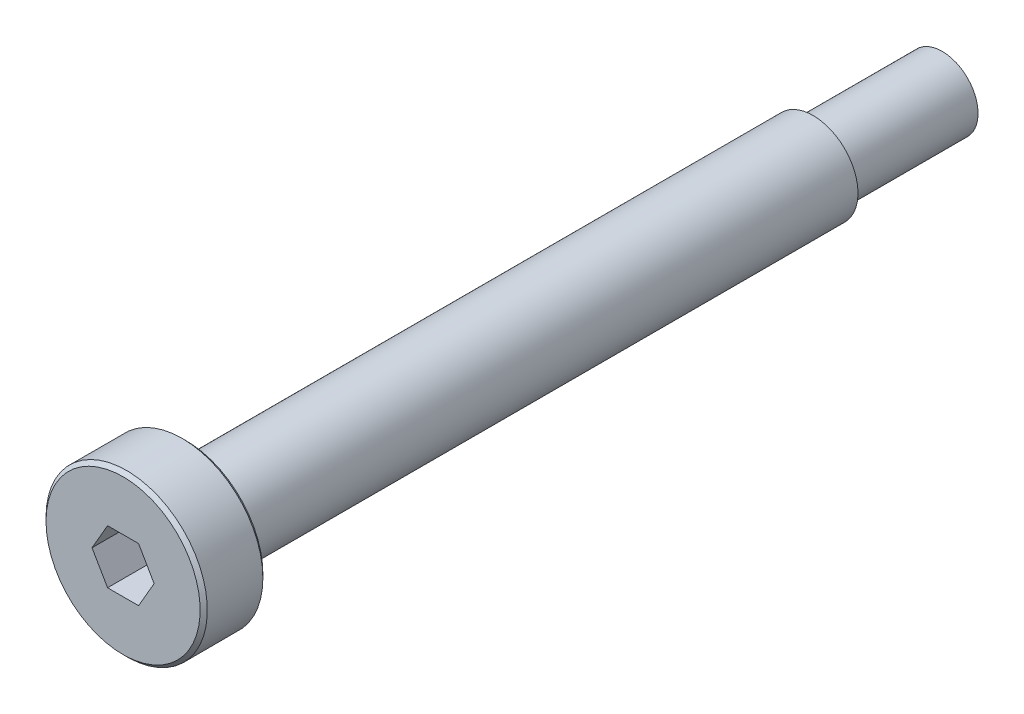
SolidWorks part; units mm, degrees
material "AISI 304"
ref_plane "前视基准面" through (0, 0, 0) normal (1, 0, 0) x (0, 1, 0)
ref_plane "上视基准面" through (0, 0, 0) normal (0, 0, 1) x (0, 1, 0)
ref_plane "右视基准面" through (0, 0, 0) normal (0, 1, 0) x (-1, 0, 0)
other "Configuration Table"
sketch "草图1" plane through (0, 0, 0) normal (1, 0, 0) x (0, 1, 0)
  line L0 (0, 0) -> (-4.5, 0)
  line L1 (-4.5, 0) -> (-4.5, -3.5)
  line L2 (-4.5, -3.5) -> (-2.5, -3.5)
  line L3 (-2.5, -3.5) -> (-2.5, -38.5)
  line L4 (-2.5, -38.5) -> (-2, -38.5)
  line L5 (-2, -38.5) -> (-2, -45.7)
  line L6 (-2, -45.7) -> (0, -45.7)
  line L7 (0, -45.7) -> (0, 0)
  point P8 (-2.25, -38.5)
  dimension "D1" = 3.5
  dimension "D2" = 35
  dimension "D3" = 7.2
  dimension "D4" = 2
  dimension "D5" = 4.5
  dimension "D6" = 2.5
revolve "旋转1" add sketch "草图1" angle 360 about L7
cosmetic thread "装饰螺纹线1"
sketch "草图2" plane through (0, 0, 0) normal (0, 0, 1) x (1, 0, 0)
  line L0 (0, 0) -> (1.7321, 0) construction
  line L1 (1.7321, 0) -> (0.866, 1.5)
  line L2 (0.866, 1.5) -> (-0.866, 1.5)
  line L3 (-0.866, 1.5) -> (-1.7321, 0)
  line L4 (-1.7321, 0) -> (-0.866, -1.5)
  line L5 (-0.866, -1.5) -> (0.866, -1.5)
  line L6 (0.866, -1.5) -> (1.7321, 0)
  circle A0 centre (0, 0) radius 1.5 construction
  dimension "D1" = 3
extrude "切除-拉伸1" cut sketch "草图2" against normal blind 3
chamfer "倒角1" distance 0.2 angle 45 2 edges at (-4.5, 0, -3.5) (-4.5, 0, 0)
sketch "草图3" plane through (0, 0, 0) normal (0, 0, 1) x (1, 0, 0)
  point P0 (0, 0)
